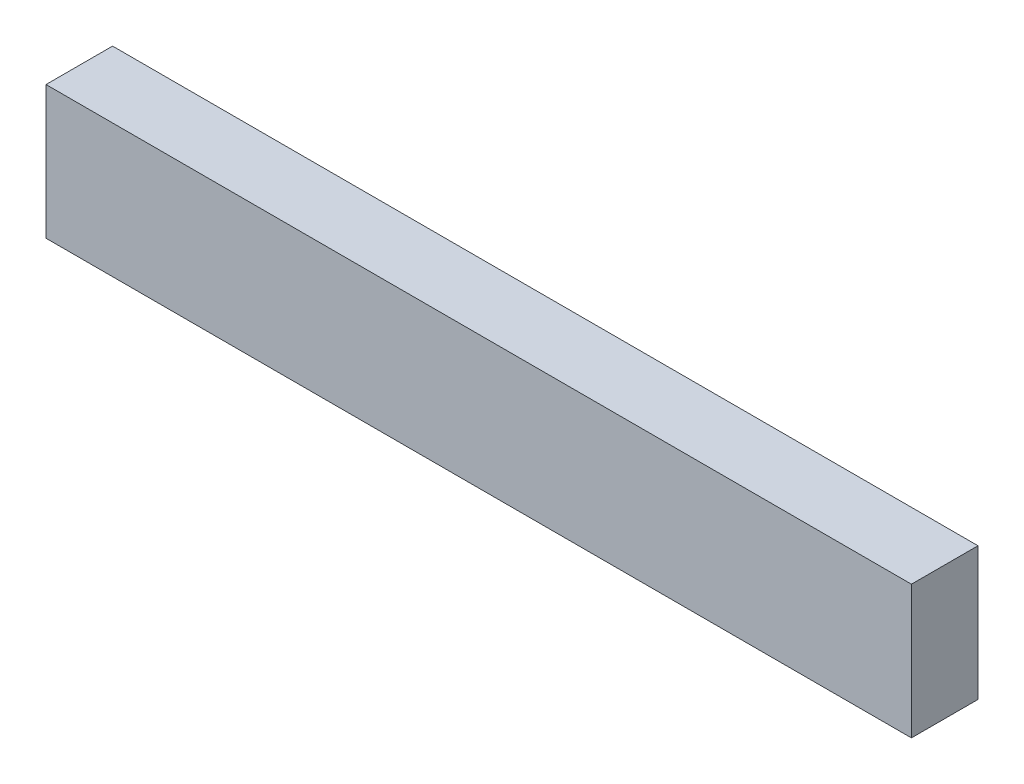
SolidWorks part; units mm, degrees
ref_plane "Front Plane" through (0, 0, 0) normal (0, 0, 1) x (1, 0, 0)
ref_plane "Top Plane" through (0, 0, 0) normal (0, 1, 0) x (1, 0, 0)
ref_plane "Right Plane" through (0, 0, 0) normal (1, 0, 0) x (0, 0, -1)
sketch "Sketch1" plane through (0, 0, 0) normal (0, 0, 1) x (1, 0, 0)
  line L0 (-65, 0) -> (65, 0) construction
  line L1 (-65, 10) -> (65, 10)
  line L2 (-65, 10) -> (-65, -10)
  line L3 (-65, -10) -> (65, -10)
  line L4 (65, 10) -> (65, -10)
  point P6 (0, 0)
  dimension "D1" = 130
  dimension "D2" = 20
extrude "Boss-Extrude1" add sketch "Sketch1" along normal blind 10
